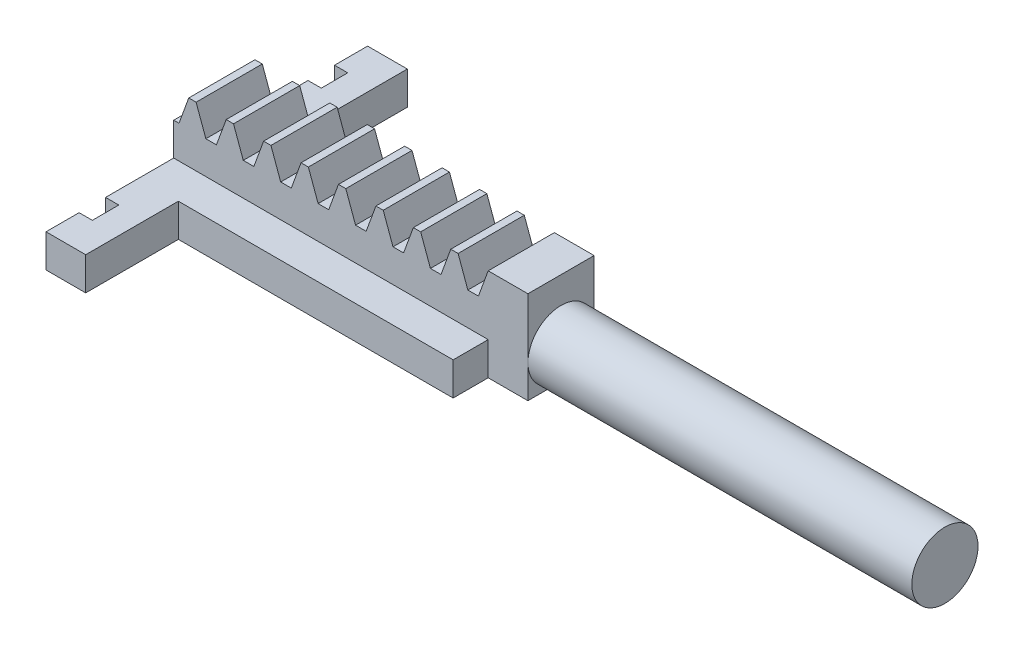
SolidWorks part; units mm, degrees
extrude "Blank" add sketch "BlankSke" against normal blind 5
sketch "BlankSke" plane through (0, 0, 0) normal (0, 0, 1) x (1, 0, 0)
  line L1 (0, 0) -> (23.757, 0)
  line L2 (0, 0) -> (0, 7)
  line L3 (0, 7) -> (23.757, 7)
  line L4 (23.757, 0) -> (23.757, 7)
  dimension "Length" = 23.757
  dimension "Blank_height" = 7
ref_plane "Plane1" through (0, 0, 0) normal (0, 0, 1) x (1, 0, 0)
ref_plane "Plane2" through (0, 0, 0) normal (0, 1, 0) x (1, 0, 0)
ref_plane "Plane3" through (0, 0, 0) normal (1, 0, 0) x (0, 0, -1)
other "Configuration Table"
sketch "HoldingSke" plane through (0, 0, 0) normal (0, 1, 0) x (1, 0, 0)
  line L0 (0, 0) -> (0.1546, 1.1003)
  line L1 (-15, 0) -> (100, 0) construction
  line L2 (0, 0) -> (-2.1039, 2.3779)
  line L3 (0, 0) -> (-11.863, 4.5341)
  line L4 (0, 0) -> (7.9495, 3.3743)
  line L5 (0, 0) -> (-23.7986, -8.8762)
  line L6 (0, 0) -> (-10.5278, -7.1032)
  line L9 (-71.009, 38.7566) -> (-14.6274, 59.2778)
  line L10 (-76.2, 3.2779) -> (-66.2, 3.2779)
  line L11 (0, 0) -> (-10, 0)
  line L12 (-76.2, 101.6) -> (-76.166, 101.6)
  line L13 (24.9733, 27.94) -> (52.9518, 28.4284)
  line L14 (24.9733, 27.94) -> (24.9743, 27.94)
  line L15 (24.9733, 27.94) -> (100.4006, 29.5858)
  circle A0 centre (0, 0) radius 19.05
  circle A1 centre (0, 0) radius 5
  circle A2 centre (0, 0) radius 12.7
  dimension "MPH" = 10
  dimension "Diameter" = 38.1
  dimension "Num_teeth" = 23
  dimension "Pitch" = 1.1111
  dimension "Show_teeth" = 998
  dimension "Thickness" = 12.7
  dimension "Ap" = 20
  dimension "Pitch_height" = 10
  dimension "Width" = 10
  dimension "Backlash" = 0.034
  dimension "Addendum_fac" = 1
  dimension "Dedendum_fac" = 1.25
  dimension "Clearance_fac" = 0.25
  dimension "Dedendum_add" = 0.001
  dimension "Length" = 60
  dimension "Module" = 0.9
sketch "TooCutSkeIll" plane through (0, 0, 0) normal (0, 0, 1) x (1, 0, 0)
  line L0 (0.2917, 6.9763) -> (-0.4535, 9.0237)
  line L1 (-0.2411, 8.875) -> (0.2411, 8.875)
  line L2 (0.4535, 9.0237) -> (-0.2917, 6.9763)
  line L3 (23.757, 7) -> (0, 7) construction
  line L4 (0, 0) -> (0, 64.897) construction
  line L5 (-13.208, 10) -> (12.954, 10) construction
  line L6 (0, 0) -> (23.757, 0) construction
  line L7 (0.8089, 10) -> (0.8089, 48.7463) construction
  line L8 (-0.8089, 10) -> (-0.8089, 48.7463) construction
  line L9 (-0.2578, 7) -> (-0.2578, 10.9254)
  line L10 (0.2578, 7) -> (0.2578, 10.9254)
  line L11 (0.2578, 10.9254) -> (-0.2578, 10.9254)
  arc A0 (0.2411, 8.875) -> (0.4535, 9.0237) centre (0.2411, 9.101) ccw
  arc A1 (-0.4535, 9.0237) -> (-0.2411, 8.875) centre (-0.2411, 9.101) ccw
  arc A2 (-0.2578, 7) -> (-0.2917, 6.9763) centre (-0.2578, 6.964) ccw
  arc A3 (0.2917, 6.9763) -> (0.2578, 7) centre (0.2578, 6.964) ccw
  dimension "Pitch_height" = 10
  dimension "Addendum_plus" = 0.9254
  dimension "Pressure_angle" = 20
  dimension "Gap_width" = 1.6177
  dimension "Dedendum" = 1.125
extrude "ToothCutIll" [suppressed] cut sketch "TooCutSkeIll" against normal through all
sketch "TooCutSkeSim" plane through (0, 0, 0) normal (0, 0, 1) x (1, 0, 0)
  line L0 (0.3994, 4.975) -> (-0.3994, 4.975)
  line L1 (1.1457, 7.0254) -> (0.3994, 4.975)
  line L2 (0, 17.4625) -> (0, 53.467) construction
  line L3 (1.1457, 7.0254) -> (-1.1457, 7.0254)
  line L6 (-1.1457, 7.0254) -> (-0.3994, 4.975)
  line L9 (-0.8089, 6.1) -> (0.8089, 6.1) construction
  line L10 (0, 0) -> (23.757, 0) construction
  line L11 (0.8089, 6.1) -> (0.8089, 53.467) construction
  line L12 (-0.8089, 6.1) -> (-0.8089, 53.467) construction
  dimension "Addendum_plus" = 0.9254
  dimension "Pitch_height" = 6.1
  dimension "Pressure_angle" = 20
  dimension "Gap_width" = 1.6177
  dimension "Dedendum" = 1.125
extrude "ToothCutSim" cut sketch "TooCutSkeSim" against normal through all
pattern_linear "TeethCuts" count 9 spacing 2.8274 along (1, 0, 0) of "ToothCutSim"
sketch "Sketch1" plane through (23.757, 0, 0) normal (1, 0, 0) x (0, 0, -1)
  line L0 (2.5, 4.975) -> (2.5, 0) construction
  line L2 (5, 0) -> (0, 0) construction
  line L3 (0, 3.5) -> (5, 3.5) construction
  line L4 (0, 0) -> (0, 7) construction
  line L5 (5, 0) -> (5, 7) construction
  circle A0 centre (2.5, 2.4875) radius 2.5
  dimension "D1" = 5
extrude "Boss-Extrude1" add sketch "Sketch1" along normal blind 32
sketch "Sketch2" plane through (0, 0, 0) normal (-1, 0, 0) x (0, 0, 1)
  line L0 (-2.5, 4.975) -> (-2.5, 0) construction
  line L1 (-7.6475, 2.5) -> (-5, 2.5)
  line L2 (-7.6475, 2.5) -> (-7.6475, 0)
  line L3 (-7.6475, 0) -> (-5, 0)
  line L4 (-5, 2.5) -> (-5, 0)
  line L5 (-7.6475, 2.5) -> (-5, 0) construction
  line L6 (-7.6475, 0) -> (-5, 2.5) construction
  line L7 (-5, 4.975) -> (0, 4.975) construction
  line L8 (-5, 0) -> (0, 0) construction
  line L9 (2.6475, 0) -> (0, 0)
  line L10 (0, 2.5) -> (0, 0)
  line L11 (2.6475, 2.5) -> (0, 2.5)
  line L12 (2.6475, 2.5) -> (2.6475, 0)
  point P0 (-6.3237, 1.25)
  dimension "D1" = 2.5
extrude "Boss-Extrude2" add sketch "Sketch2" against normal up to surface (23.757 mm away) up to face at (23.757, 0.6847, -4.4096)
sketch "Sketch3" plane through (23.757, 0, 0) normal (1, 0, 0) x (0, 0, -1)
  line L1 (0, 0) -> (5, 0)
  line L2 (0, 0) -> (0, 7)
  line L3 (0, 7) -> (5, 7)
  line L4 (5, 0) -> (5, 7)
  line L5 (0, 2.5) -> (0, 7) construction
  line L6 (5, 2.5) -> (5, 7) construction
  dimension "D1" = 7
extrude "Boss-Extrude3" add sketch "Sketch3" along normal blind 3
sketch "Sketch4" plane through (0, 0, -7.6475) normal (0, 0, -1) x (-1, 0, 0)
  line L0 (-23.757, 0) -> (0, 0) construction
  line L1 (-3, 2.5) -> (0, 2.5)
  line L2 (-3, 2.5) -> (-3, 0)
  line L3 (-3, 0) -> (0, 0)
  line L4 (0, 2.5) -> (0, 0)
  line L5 (-3, 2.5) -> (0, 0) construction
  line L6 (-3, 0) -> (0, 2.5) construction
  line L7 (-23.757, 2.5) -> (0, 2.5) construction
  line L8 (0, 2.5) -> (0, 0) construction
  point P0 (-1.5, 1.25)
  dimension "D1" = 3
extrude "Boss-Extrude4" add sketch "Sketch4" along normal blind 7
ref_plane "Plane4" through (0, 0, -2.5) normal (0, 0, -1) x (-1, 0, 0)
mirror "Mirror1" about plane through (0, 0, -2.5) normal (0, 0, -1) of "Boss-Extrude4"
sketch "Sketch5" plane through (0, 0, 0) normal (-1, 0, 0) x (0, 0, 1)
  line L0 (-14.6475, 0) -> (9.6475, 0) construction
  line L1 (-12.1475, 2.5) -> (-10.1475, 2.5)
  line L2 (-12.1475, 2.5) -> (-12.1475, 0)
  line L3 (-12.1475, 0) -> (-10.1475, 0)
  line L4 (-10.1475, 2.5) -> (-10.1475, 0)
  line L5 (-12.1475, 2.5) -> (-10.1475, 0) construction
  line L6 (-12.1475, 0) -> (-10.1475, 2.5) construction
  line L7 (-5, 2.5) -> (-14.6475, 2.5) construction
  line L8 (-14.6475, 0) -> (-14.6475, 2.5) construction
  point P0 (-11.1475, 1.25)
  dimension "D1" = 2.5
  dimension "D2" = 2
extrude "Cut-Extrude1" cut sketch "Sketch5" against normal blind 1
ref_plane "Plane5" through (0, 0, -2.5) normal (0, 0, -1) x (-1, 0, 0)
mirror "Mirror2" about plane through (0, 0, -2.5) normal (0, 0, -1) of "Cut-Extrude1"
equation "' \"Module@HoldingSke\" = 6.35"
equation "' \"Num_teeth@HoldingSke\" = 12"
equation "' \"Ap@HoldingSke\" =  20"
equation "' \"Ap@HoldingSke\" = 20"
equation "' \"Width@HoldingSke\" = 0.25 * 25.4"
equation "' \"Show_teeth@HoldingSke\" = 500"
equation "' \"Backlash@HoldingSke\" = 0.009 * 25.4"
equation "' \"Addendum_fac@HoldingSke\" = 1.0"
equation "' \"Dedendum_fac@HoldingSke\" = 1.25"
equation "' \"Dedendum_add@HoldingSke\" = 0.00005 * 25.4"
equation "' \"Clearance_fac@HoldingSke\" = 0.25"
equation "' \"Pitch_height@HoldingSke\" = 1 * 25.4"
equation "' \"Length@HoldingSke\" = 4.71 * 25.4"
equation "\"Pitch@HoldingSke\" = 1 / \"Module@HoldingSke\""
equation "\"MPH@HoldingSke\" = \"Dedendum_fac@HoldingSke\" / \"Pitch@HoldingSke\" + 2 * \"Dedendum_add@HoldingSke\" + 0.002 * 25.4"
equation "\"MPH@HoldingSke\" = ((sgn( \"MPH@HoldingSke\" - \"Pitch_height@HoldingSke\")+1)*( \"MPH@HoldingSke\" - \"Pitch_height@HoldingSke\"))/2 + \"Pitch_height@HoldingSke\""
equation "\"Pressure_angle@TooCutSkeIll\" = \"Ap@HoldingSke\""
equation "\"Addendum_plus@TooCutSkeIll\" =  \"Addendum_fac@HoldingSke\"  / \"Pitch@HoldingSke\" + 0.001 *25.4"
equation "\"Dedendum@TooCutSkeIll\" = \"Dedendum_fac@HoldingSke\"  / \"Pitch@HoldingSke\""
equation "\"Pitch_height@TooCutSkeIll\" =  \"MPH@HoldingSke\""
equation "\"Gap_width@TooCutSkeIll\" = 3.14159265 / 2 / \"Pitch@HoldingSke\" + 6 * \"Backlash@HoldingSke\""
equation "\"Pressure_angle@TooCutSkeSim\" = \"Ap@HoldingSke\""
equation "\"Addendum_plus@TooCutSkeSim\" =  \"Addendum_fac@HoldingSke\"  / \"Pitch@HoldingSke\" + 0.001 * 25.4"
equation "\"Dedendum@TooCutSkeSim\" = \"Dedendum_fac@HoldingSke\"  / \"Pitch@HoldingSke\""
equation "\"Gap_width@TooCutSkeSim\" = 3.14159265 / 2 / \"Pitch@HoldingSke\" + 6 * \"Backlash@HoldingSke\""
equation "\"Root_fillet@TooCutSkeIll\" = \"Clearance_fac@HoldingSke\" / \"Pitch@HoldingSke\" + \"Dedendum_add@HoldingSke\""
equation "\"Break_rad@TooCutSkeIll\" = 0.02 / \"Pitch@HoldingSke\" * 2"
equation "\"Linear_pitch@TeethCuts\" = 3.14159265 / \"Pitch@HoldingSke\""
equation "\"Num_teeth@HoldingSke\" = int( ( \"Length@HoldingSke\" + 0 ) / (3.14159265 / \"Pitch@HoldingSke\")) + 0.9999  + 1"
equation " \"Num_teeth@TeethCuts\" = ((sgn( \"Num_teeth@TeethCuts\" - 2.0)+1)*( \"Num_teeth@TeethCuts\" - 2.0))/2 +2.0"
